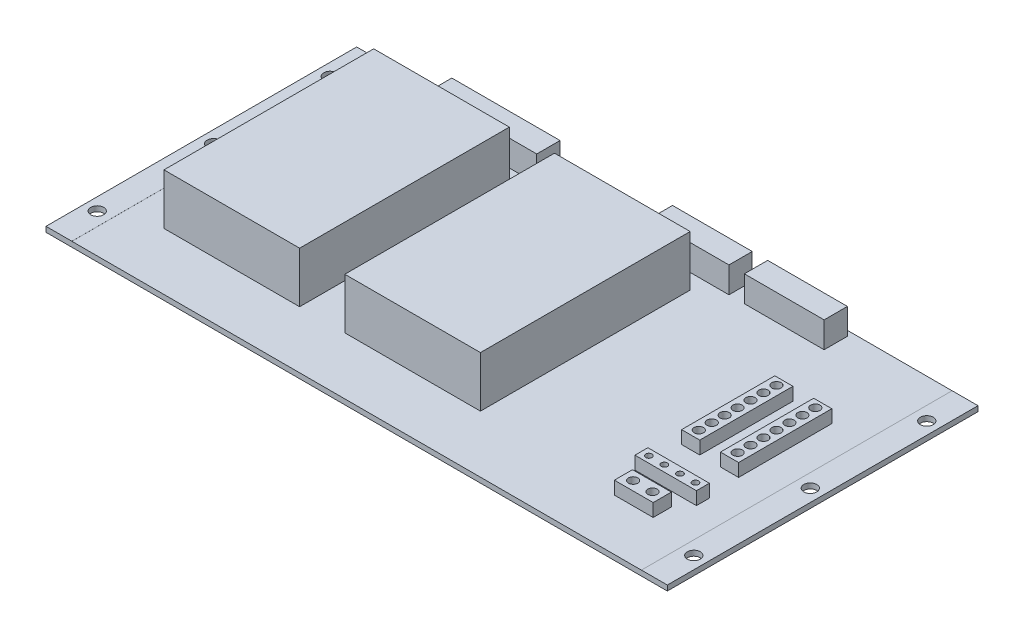
SolidWorks part; units mm, degrees
ref_plane "Front Plane" through (0, 0, 0) normal (0, 0, 1) x (1, 0, 0)
ref_plane "Top Plane" through (0, 0, 0) normal (0, 1, 0) x (1, 0, 0)
ref_plane "Right Plane" through (0, 0, 0) normal (1, 0, 0) x (0, 0, -1)
sketch "Sketch1" plane through (0, 0, 0) normal (0, 1, 0) x (1, 0, 0)
  line L0 (152.4, 152.4) -> (152.4, 0) construction
  line L1 (0, 0) -> (304.8, 0)
  line L2 (0, 0) -> (0, 152.4)
  line L3 (0, 152.4) -> (304.8, 152.4)
  line L4 (304.8, 0) -> (304.8, 152.4)
  line L5 (0, 76.2) -> (304.8, 76.2) construction
  circle A0 centre (298.7313, 76.2) radius 3.175
  circle A1 centre (298.7313, 133.35) radius 3.175
  circle A2 centre (298.7313, 19.05) radius 3.175
  circle A3 centre (6.0687, 19.05) radius 3.175
  circle A4 centre (6.0687, 76.2) radius 3.175
  circle A5 centre (6.0687, 133.35) radius 3.175
  dimension "D1" = 152.4
  dimension "D2" = 304.8
extrude "Board" add sketch "Sketch1" along normal blind 2.54
sketch "Sketch2" plane through (0, 2.54, 0) normal (0, 1, 0) x (-1, 0, 0)
  line L1 (-29.8192, -130.9204) -> (-96.3672, -130.9204)
  line L2 (-29.8192, -130.9204) -> (-29.8192, -28.0504)
  line L3 (-29.8192, -28.0504) -> (-96.3672, -28.0504)
  line L4 (-96.3672, -130.9204) -> (-96.3672, -28.0504)
  line L5 (-118.5247, -28.0504) -> (-185.0727, -28.0504)
  line L6 (-118.5247, -28.0504) -> (-118.5247, -130.9204)
  line L7 (-118.5247, -130.9204) -> (-185.0727, -130.9204)
  line L8 (-185.0727, -28.0504) -> (-185.0727, -130.9204)
  dimension "D1" = 66.548
  dimension "D2" = 102.87
  dimension "D3" = 102.87
  dimension "D4" = 66.548
extrude "Accelnet" add sketch "Sketch2" along normal blind 24.892
sketch "Sketch3" plane through (0, 2.54, 0) normal (0, 1, 0) x (-1, 0, 0)
  line L1 (-49.2246, -138.43) -> (-102.3106, -138.43)
  line L2 (-49.2246, -138.43) -> (-49.2246, -149.86)
  line L3 (-49.2246, -149.86) -> (-102.3106, -149.86)
  line L4 (-102.3106, -138.43) -> (-102.3106, -149.86)
  dimension "D1" = 53.086
  dimension "D2" = 11.43
extrude "D25toComputer" add sketch "Sketch3" along normal blind 12.7
sketch "Sketch5" plane through (0, 2.54, 0) normal (0, 1, 0) x (-1, 0, 0)
  line L1 (-157.4805, -138.43) -> (-196.5965, -138.43)
  line L2 (-157.4805, -138.43) -> (-157.4805, -149.86)
  line L3 (-157.4805, -149.86) -> (-196.5965, -149.86)
  line L4 (-196.5965, -138.43) -> (-196.5965, -149.86)
  line L6 (-204.1573, -138.43) -> (-243.2733, -138.43)
  line L7 (-204.1573, -138.43) -> (-204.1573, -149.86)
  line L8 (-204.1573, -149.86) -> (-243.2733, -149.86)
  line L9 (-243.2733, -138.43) -> (-243.2733, -149.86)
  dimension "D1" = 39.116
  dimension "D2" = 39.116
  dimension "D3" = 11.43
  dimension "D4" = 11.43
extrude "D15toMotor/Brake" add sketch "Sketch5" along normal blind 12.7
sketch "Sketch7" plane through (0, 2.54, 0) normal (0, 1, 0) x (-1, 0, 0)
  line L0 (-272.6248, -34.1299) -> (-272.6248, -25.2399)
  line L1 (-263.0998, -34.1299) -> (-263.0998, -25.2399) construction
  line L2 (-253.5748, -29.6849) -> (-272.6248, -29.6849) construction
  line L3 (-270.6511, -47.2422) -> (-270.6511, -40.8922) construction
  line L5 (-278.1876, -40.8922) -> (-248.012, -40.8922)
  line L6 (-272.6248, -25.2399) -> (-253.5748, -25.2399)
  line L8 (-272.6248, -34.1299) -> (-253.5748, -34.1299)
  line L9 (-253.5748, -25.2399) -> (-253.5748, -34.1299)
  line L10 (-278.1876, -40.8922) -> (-278.1876, -47.2422)
  line L11 (-278.1876, -44.0672) -> (-263.1146, -44.0672) construction
  line L12 (-263.0998, -47.2422) -> (-263.0998, -40.8922) construction
  line L13 (-248.012, -40.8922) -> (-248.012, -47.2422)
  line L14 (-248.012, -44.0672) -> (-263.0849, -44.0672) construction
  line L15 (-255.5485, -47.2422) -> (-255.5485, -40.8922) construction
  line L16 (-278.1876, -47.2422) -> (-248.012, -47.2422)
  circle A0 centre (-258.3544, -29.6849) radius 2.286
  circle A1 centre (-267.8451, -29.6849) radius 2.286
  circle A2 centre (-266.9381, -44.0672) radius 1.524
  circle A3 centre (-274.5311, -44.0672) radius 1.524
  circle A4 centre (-251.6684, -44.0672) radius 1.524
  circle A5 centre (-259.2615, -44.0672) radius 1.524
  point P12 (0, 0)
  dimension "D3" = 19.05
  dimension "D4" = 8.89
extrude "HVin/24Vin/5Vin" add sketch "Sketch7" along normal blind 6.35
sketch "Sketch9" plane through (0, 2.54, 0) normal (0, 1, 0) x (-1, 0, 0)
  line L12 (-276.5507, -108.9227) -> (-276.5507, -63.2027)
  line L13 (-272.1057, -108.9227) -> (-272.1057, -63.2027) construction
  line L14 (-248.6107, -108.9227) -> (-257.5007, -108.9227)
  line L15 (-267.6607, -108.9227) -> (-276.5507, -108.9227)
  line L16 (-253.0557, -108.9227) -> (-253.0557, -63.2027) construction
  line L17 (-248.6107, -108.9227) -> (-248.6107, -63.2027)
  line L18 (-248.6107, -63.2027) -> (-257.5007, -63.2027)
  line L19 (-267.6607, -86.0627) -> (-276.5507, -86.0627) construction
  line L20 (-267.6607, -108.9227) -> (-267.6607, -63.2027)
  line L21 (-257.5007, -108.9227) -> (-257.5007, -63.2027)
  line L22 (-267.6607, -63.2027) -> (-276.5507, -63.2027)
  line L23 (-248.6107, -86.0627) -> (-257.5007, -86.0627) construction
  circle A14 centre (-272.1057, -73.5242) radius 2.286
  circle A15 centre (-253.0557, -79.8742) radius 2.286
  circle A16 centre (-253.0557, -67.1742) radius 2.286
  circle A17 centre (-272.1057, -67.1742) radius 2.286
  circle A18 centre (-272.1057, -86.2242) radius 2.286
  circle A19 centre (-272.1057, -79.8742) radius 2.286
  circle A20 centre (-272.1057, -98.9242) radius 2.286
  circle A21 centre (-253.0557, -98.9242) radius 2.286
  circle A22 centre (-253.0557, -105.2742) radius 2.286
  circle A23 centre (-272.1057, -92.5742) radius 2.286
  circle A24 centre (-272.1057, -105.2742) radius 2.286
  circle A25 centre (-253.0557, -73.5242) radius 2.286
  circle A26 centre (-253.0557, -86.2242) radius 2.286
  circle A27 centre (-253.0557, -92.5742) radius 2.286
extrude "Motors/Brakes" add sketch "Sketch9" along normal blind 6.35
sketch "Sketch10" plane through (0, 2.54, 0) normal (0, 1, 0) x (-1, 0, 0)
  line L0 (-304.8, -152.4) -> (0, -152.4) construction
  line L1 (-304.8, 0) -> (-292.1, 0)
  line L2 (-304.8, 0) -> (-304.8, -152.4)
  line L3 (-304.8, -152.4) -> (-292.1, -152.4)
  line L4 (-292.1, 0) -> (-292.1, -152.4)
  line L5 (-152.4, 0) -> (-152.4, -152.4) construction
  line L6 (0, 0) -> (-304.8, 0) construction
  line L7 (-304.8, -152.4) -> (0, -152.4) construction
  line L8 (-12.7, 0) -> (-12.7, -152.4)
  line L9 (0, -152.4) -> (-12.7, -152.4)
  line L10 (0, 0) -> (0, -152.4)
  line L11 (0, 0) -> (-12.7, 0)
  line L12 (-304.8, -76.2) -> (0, -76.2) construction
  circle A0 centre (-298.7313, -133.35) radius 3.175
  circle A1 centre (-298.7313, -76.2) radius 3.175
  circle A2 centre (-298.7313, -19.05) radius 3.175
  circle A3 centre (-6.0687, -19.05) radius 3.175
  circle A4 centre (-6.0687, -76.2) radius 3.175
  circle A5 centre (-6.0687, -133.35) radius 3.175
  dimension "D1" = 12.7
extrude "platedEdge" add sketch "Sketch10" along normal blind 0.0254
